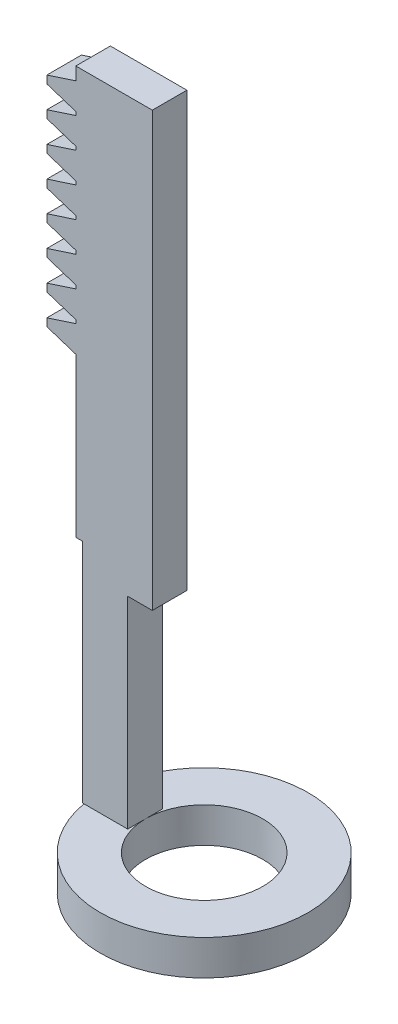
SolidWorks part; units mm, degrees
ref_plane "Front Plane" through (0, 0, 0) normal (0, 0, 1) x (1, 0, 0)
ref_plane "Top Plane" through (0, 0, 0) normal (0, 1, 0) x (1, 0, 0)
ref_plane "Right Plane" through (0, 0, 0) normal (1, 0, 0) x (0, 0, -1)
sketch "Sketch2" plane through (0, 0, 0) normal (0, 0, 1) x (1, 0, 0)
  line L0 (9.3016, 48.4437) -> (9.3016, -20.4372)
  line L1 (9.3016, -20.4372) -> (4.9607, -20.4372)
  line L2 (-4.1984, 48.4437) -> (-4.1984, -16.02)
  line L3 (-4.1984, 33.1607) -> (-9.3016, 34.8184)
  line L4 (9.3016, 48.4437) -> (9.3016, 56.02)
  line L5 (-9.3016, 34.8184) -> (-9.3016, 36.186)
  line L6 (-9.3016, 36.186) -> (-4.1984, 37.8437)
  line L7 (-9.3016, 30.886) -> (-4.1984, 32.5437)
  line L8 (-9.3016, 29.5184) -> (-9.3016, 30.886)
  line L9 (-4.1984, 27.8607) -> (-9.3016, 29.5184)
  line L10 (-9.3016, 25.586) -> (-4.1984, 27.2437)
  line L11 (-9.3016, 24.2184) -> (-9.3016, 25.586)
  line L12 (-4.1984, 22.5607) -> (-9.3016, 24.2184)
  line L13 (-9.3016, 20.286) -> (-4.1984, 21.9437)
  line L14 (-9.3016, 18.9184) -> (-9.3016, 20.286)
  line L15 (-4.1984, 17.2607) -> (-9.3016, 18.9184)
  line L16 (-9.3016, 14.986) -> (-4.1984, 16.6437)
  line L17 (-9.3016, 13.6184) -> (-9.3016, 14.986)
  line L18 (-4.1984, 11.9607) -> (-9.3016, 13.6184)
  line L28 (-9.3016, 41.486) -> (-4.1984, 43.1437)
  line L29 (-9.3016, 40.1184) -> (-9.3016, 41.486)
  line L30 (-4.1984, 38.4607) -> (-9.3016, 40.1184)
  line L31 (-9.3016, 46.786) -> (-4.1984, 48.4437)
  line L32 (-9.3016, 45.4184) -> (-9.3016, 46.786)
  line L33 (-4.1984, 43.7607) -> (-9.3016, 45.4184)
  line L34 (9.3016, 56.02) -> (-4.1984, 56.02)
  line L35 (-4.1984, -16.02) -> (-3.0393, -16.02)
  line L36 (4.9607, -20.4372) -> (4.9607, -56.02)
  line L37 (4.9607, -56.02) -> (-3.0393, -56.02)
  line L38 (-3.0393, -16.02) -> (-3.0393, -56.02)
  line L39 (-4.1984, 56.02) -> (-4.1984, 48.4437)
  line L40 (-4.1984, 49.0637) -> (-9.3016, 50.7215)
  line L41 (-9.3016, 50.7215) -> (-9.3016, 52.089)
  line L42 (-9.3016, 52.089) -> (-4.1984, 53.7468)
extrude "Boss-Extrude1" add sketch "Sketch2" along normal blind 6.1 contours L34 L39 L2 L35 L38 L37 L36 L1 L0 L4 | L42 L41 L40 L39 | L33 L2 L31 L32 | L30 L2 L28 L29 | L6 L5 L3 L2 | L9 L2 L7 L8 | L12 L2 L10 L11 | L15 L2 L13 L14 | L18 L2 L16 L17
sketch "Sketch3" plane through (0, -56.02, 0) normal (0, -1, 0) x (1, 0, 0)
  line L1 (9.3016, 6.1) -> (9.3016, 0) construction
  line L2 (-3.0393, 6.1) -> (-3.0393, 0) construction
  circle A0 centre (15.3016, 2.9426) radius 18.3408
  circle A1 centre (15.3016, 2.9426) radius 10.3408
  dimension "D1" = 6
extrude "Boss-Extrude2" add sketch "Sketch3" along normal blind 6.2
